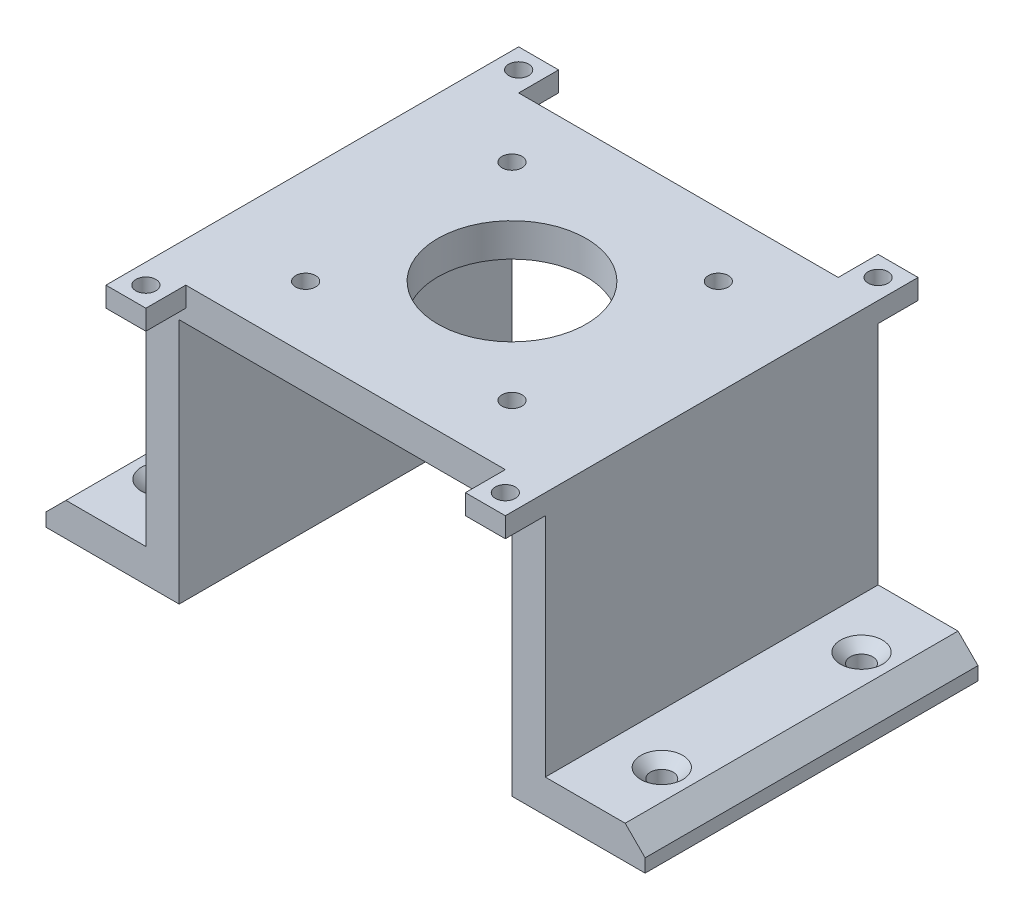
SolidWorks part; units mm, degrees
ref_plane "Front Plane" through (0, 0, 0) normal (0, 0, 1) x (1, 0, 0)
ref_plane "Top Plane" through (0, 0, 0) normal (0, 1, 0) x (1, 0, 0)
ref_plane "Right Plane" through (0, 0, 0) normal (1, 0, 0) x (0, 0, -1)
sketch "Sketch2" plane through (0, 0, 0) normal (0, 0, 1) x (1, 0, 0)
  line L0 (0, 0) -> (0, 37)
  line L1 (0, 37) -> (-50, 37)
  line L4 (-50, 42) -> (5, 42)
  line L5 (5, 42) -> (5, 5)
  line L6 (0, 0) -> (20, 0)
  line L9 (5, 5) -> (20, 5)
  line L10 (20, 0) -> (20, 5)
  line L11 (-25, 37) -> (-25, -6.2666) construction
  line L12 (-70, 0) -> (-70, 5)
  line L13 (-50, 0) -> (-70, 0)
  line L14 (-55, 5) -> (-70, 5)
  line L15 (-55, 42) -> (-55, 5)
  line L16 (-50, 0) -> (-50, 37)
  line L17 (-50, 42) -> (-55, 42)
  dimension "D1" = 37
  dimension "D2" = 50
  dimension "D3" = 5
  dimension "D4" = 5
  dimension "D5" = 5
  dimension "D6" = 15
  dimension "D7" = 5
extrude "Boss-Extrude1" add sketch "Sketch2" along normal blind 50
sketch "Sketch6" plane through (0, 5, 0) normal (0, 1, 0) x (1, 0, 0)
  line L0 (-55, 0) -> (-70, 0) construction
  line L1 (-55, -50) -> (-70, -50) construction
  line L2 (5, 0) -> (-55, 0) construction
  line L3 (-25, 0) -> (-25, -50) construction
  line L4 (5, -50) -> (-55, -50) construction
  line L6 (-55, -50) -> (-55, 0) construction
  point P0 (-62.5, -10)
  point P2 (-62.5, -40)
  point P17 (12.5, -40)
  point P18 (12.5, -10)
  dimension "D1" = 10
  dimension "D2" = 10
  dimension "D3" = 7.5
  dimension "D4" = 7.5
hole_wizard "CSK for M3 Flat Head Machine Screw1" positions "Sketch6" profile "Sketch7" countersink size "M3" standard "ANSI Metric" end condition through all
sketch "Sketch7" plane through (-62.5, 5, 10) normal (1, 0, 0) x (0, 0, 1)
  line L0 (0, 0) -> (0, 5)
  line L1 (0, 5) -> (1.7, 5)
  line L2 (1.7, 5) -> (1.7, 1.45)
  line L3 (1.7, 1.45) -> (3.15, 0)
  line L5 (3.15, 0) -> (0, 0)
  line L6 (-1.7, 1.45) -> (-3.15, 0) construction
  line L11 (0, -6.35) -> (0, 107.95) construction
  dimension "Thru Hole Dia." = 3.4
  dimension "Thru Hole Depth" = 5
  dimension "Near C'Sink Dia." = 6.3
  dimension "Near C'Sink Angle" = 90
sketch "Sketch8" plane through (0, 42, 0) normal (0, 1, 0) x (1, 0, 0)
  line L0 (-55, -25) -> (5, -25) construction
  line L1 (-55, -50) -> (-55, 0) construction
  line L2 (5, -50) -> (5, 0) construction
  line L3 (-25, 0) -> (-25, -50) construction
  line L4 (5, 0) -> (-55, 0) construction
  line L5 (5, -50) -> (-55, -50) construction
  circle A0 centre (-25, -25) radius 11.15
  dimension "D1" = 22.3
extrude "Cut-Extrude1" cut sketch "Sketch8" against normal blind 41 contours A0
sketch "Sketch10" plane through (0, 42, 0) normal (0, 1, 0) x (1, 0, 0)
  line L0 (-55, -25) -> (5, -25) construction
  line L1 (-55, -50) -> (-55, 0) construction
  line L2 (5, -50) -> (5, 0) construction
  line L3 (-25, -50) -> (-25, 0) construction
  line L4 (5, -50) -> (-55, -50) construction
  line L5 (5, 0) -> (-55, 0) construction
  circle A0 centre (-40.5, -9.5) radius 1.5
  circle A1 centre (-9.5, -9.5) radius 1.5
  circle A2 centre (-9.5, -40.5) radius 1.5
  circle A3 centre (-40.5, -40.5) radius 1.5
  point P12 (-40.5, -9.5)
  point P15 (-9.5, -9.5)
  point P17 (-9.5, -40.5)
  point P19 (-40.5, -40.5)
  dimension "D1" = 3
  dimension "D2" = 15.5
  dimension "D3" = 15.5
hole_wizard "Ø3.0 (3) Diameter Hole1" positions "Sketch10" profile "Sketch12" hole size "Ø3.0" standard "ANSI Metric" end condition through all
sketch "Sketch12" plane through (-40.5, 42, 40.5) normal (1, 0, 0) x (0, 0, 1)
  line L0 (0, 0) -> (0, 42)
  line L1 (0, 42) -> (1.5, 42)
  line L2 (1.5, 42) -> (1.5, 0)
  line L5 (1.5, 0) -> (0, 0)
  line L11 (0, -6.35) -> (0, 107.95) construction
  dimension "Thru Hole Dia." = 3
  dimension "Thru Hole Depth" = 42
chamfer "Chamfer1" distance 3 angle 45 2 edges at (20, 5, 25) (-70, 5, 25)
sketch "Sketch14" plane through (0, 42, 0) normal (0, 1, 0) x (1, 0, 0)
  line L0 (-25, -50) -> (-25, 0) construction
  line L1 (-55, 0) -> (-49, 0)
  line L2 (-55, 0) -> (-55, 6)
  line L3 (-55, 6) -> (-49, 6)
  line L4 (-49, 0) -> (-49, 6)
  line L5 (5, -50) -> (-55, -50) construction
  line L6 (5, 0) -> (-55, 0) construction
  line L7 (-55, -25) -> (5, -25) construction
  line L8 (-55, -50) -> (-55, 0) construction
  line L9 (5, -50) -> (5, 0) construction
  line L10 (-55, -50) -> (-55, -56)
  line L11 (-55, -50) -> (-49, -50)
  line L12 (-49, -50) -> (-49, -56)
  line L13 (-55, -56) -> (-49, -56)
  line L14 (-1, 0) -> (-1, 6)
  line L15 (5, 6) -> (-1, 6)
  line L16 (5, 0) -> (5, 6)
  line L17 (5, 0) -> (-1, 0)
  line L18 (5, -56) -> (-1, -56)
  line L19 (-1, -50) -> (-1, -56)
  line L20 (5, -50) -> (-1, -50)
  line L21 (5, -50) -> (5, -56)
  dimension "D1" = 6
  dimension "D2" = 6
extrude "Boss-Extrude2" add sketch "Sketch14" against normal blind 3
sketch "Sketch17" plane through (0, 42, 0) normal (0, 1, 0) x (1, 0, 0)
  line L0 (-49, 0) -> (-49, 6) construction
  line L1 (-49, 6) -> (-55, 6) construction
  line L2 (-25, -50) -> (-25, 0) construction
  line L3 (-1, -50) -> (-49, -50) construction
  line L4 (-1, 0) -> (-49, 0) construction
  line L6 (-55, -25) -> (5, -25) construction
  line L7 (-55, -56) -> (-55, 6) construction
  line L8 (5, -56) -> (5, 6) construction
  point P0 (-52, 3)
  point P23 (2, 3)
  point P24 (2, -53)
  point P25 (-52, -53)
  dimension "D1" = 3
  dimension "D2" = 3
hole_wizard "Ø3.0 (3) Diameter Hole2" positions "Sketch17" profile "Sketch18" hole size "Ø3.0" standard "ANSI Metric" end condition through all
sketch "Sketch18" plane through (-52, 42, -3) normal (1, 0, 0) x (0, 0, 1)
  line L0 (0, 0) -> (0, 42)
  line L1 (0, 42) -> (1.5, 42)
  line L2 (1.5, 42) -> (1.5, 0)
  line L5 (1.5, 0) -> (0, 0)
  line L11 (0, -6.35) -> (0, 107.95) construction
  dimension "Thru Hole Dia." = 3
  dimension "Thru Hole Depth" = 42
